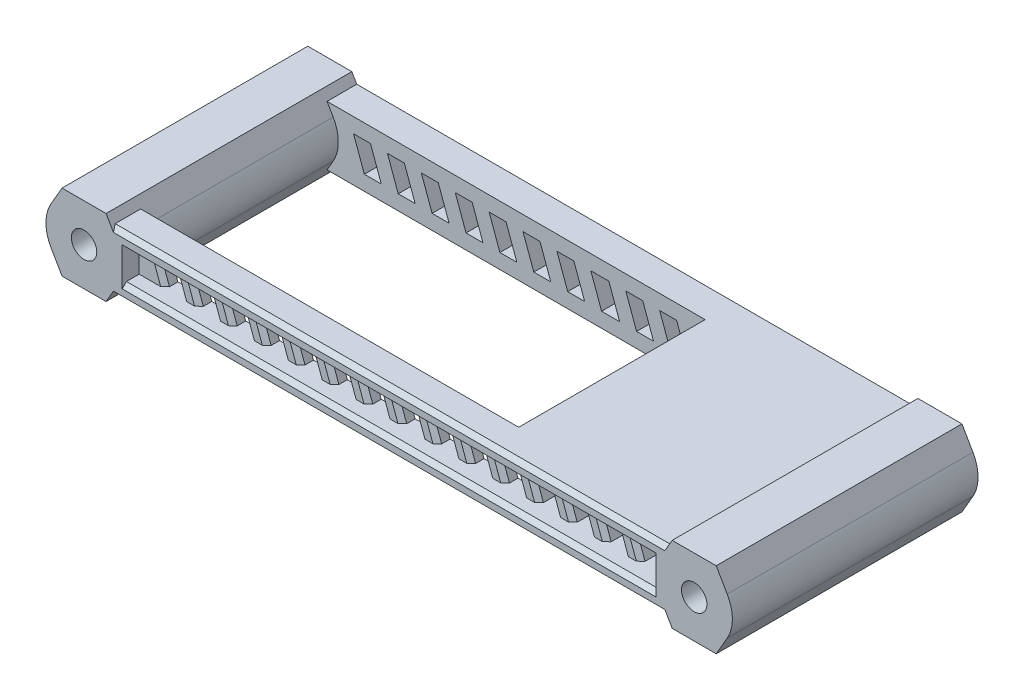
SolidWorks part; units mm, degrees
ref_plane "Front Plane" through (0, 0, 0) normal (0, 0, 1) x (1, 0, 0)
ref_plane "Top Plane" through (0, 0, 0) normal (0, 1, 0) x (1, 0, 0)
ref_plane "Right Plane" through (0, 0, 0) normal (1, 0, 0) x (0, 0, -1)
sketch "Sketch1" plane through (0, 0, 0) normal (0, 0, 1) x (1, 0, 0)
  line L0 (-36, 0) -> (36, 0) construction
  line L1 (0, -10.8775) -> (0, 10.3925) construction
  line L2 (-30.8038, 0) -> (-33.4019, 4.5)
  line L3 (-33.4019, 4.5) -> (-38.5981, 4.5)
  line L4 (-38.5981, 4.5) -> (-41.1962, 0)
  line L5 (-41.1962, 0) -> (-38.5981, -4.5)
  line L6 (-38.5981, -4.5) -> (-33.4019, -4.5)
  line L7 (-33.4019, -4.5) -> (-30.8038, 0)
  line L8 (-32.8246, 3.5) -> (32.8246, 3.5)
  line L9 (32.8246, -3.5) -> (-32.8246, -3.5)
  line L10 (31.5, 1.75) -> (-31.5, 1.75)
  line L11 (-31.5, 1.75) -> (-31.5, -1.75)
  line L12 (-31.5, -1.75) -> (31.5, -1.75)
  line L13 (31.5, 1.75) -> (31.5, -1.75)
  line L14 (33.4019, -4.5) -> (30.8038, 0)
  line L15 (38.5981, -4.5) -> (33.4019, -4.5)
  line L16 (41.1962, 0) -> (38.5981, -4.5)
  line L17 (38.5981, 4.5) -> (41.1962, 0)
  line L18 (33.4019, 4.5) -> (38.5981, 4.5)
  line L19 (30.8038, 0) -> (33.4019, 4.5)
  line L20 (-1.7011, 1.75) -> (-0.4272, -1.75)
  line L21 (0.4272, 1.75) -> (1.7011, -1.75)
  line L22 (-2.4136, 6.6312) -> (2.4136, -6.6312) construction
  line L23 (2.4272, 1.75) -> (3.7011, -1.75)
  line L24 (4.4272, 1.75) -> (5.7011, -1.75)
  line L25 (6.4272, 1.75) -> (7.7011, -1.75)
  line L26 (8.4272, 1.75) -> (9.7011, -1.75)
  line L27 (10.4272, 1.75) -> (11.7011, -1.75)
  line L28 (12.4272, 1.75) -> (13.7011, -1.75)
  line L29 (14.4272, 1.75) -> (15.7011, -1.75)
  line L30 (16.4272, 1.75) -> (17.7011, -1.75)
  line L31 (18.4272, 1.75) -> (19.7011, -1.75)
  line L32 (20.4272, 1.75) -> (21.7011, -1.75)
  line L33 (22.4272, 1.75) -> (23.7011, -1.75)
  line L34 (24.4272, 1.75) -> (25.7011, -1.75)
  line L35 (26.4272, 1.75) -> (27.7011, -1.75)
  line L36 (28.4272, 1.75) -> (29.7011, -1.75)
  line L38 (-3.7011, 1.75) -> (-2.4272, -1.75)
  line L39 (-5.7011, 1.75) -> (-4.4272, -1.75)
  line L40 (-7.7011, 1.75) -> (-6.4272, -1.75)
  line L41 (-9.7011, 1.75) -> (-8.4272, -1.75)
  line L42 (-11.7011, 1.75) -> (-10.4272, -1.75)
  line L43 (-13.7011, 1.75) -> (-12.4272, -1.75)
  line L44 (-15.7011, 1.75) -> (-14.4272, -1.75)
  line L45 (-17.7011, 1.75) -> (-16.4272, -1.75)
  line L46 (-19.7011, 1.75) -> (-18.4272, -1.75)
  line L47 (-21.7011, 1.75) -> (-20.4272, -1.75)
  line L48 (-23.7011, 1.75) -> (-22.4272, -1.75)
  line L49 (-25.7011, 1.75) -> (-24.4272, -1.75)
  line L50 (-27.7011, 1.75) -> (-26.4272, -1.75)
  line L51 (-29.7011, 1.75) -> (-28.4272, -1.75)
  line L53 (-31.7011, 1.75) -> (-30.4272, -1.75)
  line L54 (30.4272, 1.75) -> (31.7011, -1.75)
  circle A0 centre (-36, 0) radius 1.5
  circle A1 centre (-36, 0) radius 4.5 construction
  circle A2 centre (36, 0) radius 4.5 construction
  circle A3 centre (36, 0) radius 1.5
  point P24 (0, -1.75)
  point P25 (0, 1.75)
  point P26 (0, -3.5)
  point P27 (0, 3.5)
  dimension "D1" = 9
  dimension "D2" = 3
  dimension "D3" = 36
  dimension "D4" = 3.5
  dimension "D5" = 1.75
  dimension "D6" = 70
  dimension "D7" = 1
  dimension "D8" = 16
  dimension "D9" = 16
sketch "Sketch2" plane through (0, 0, 0) normal (0, 0, 1) x (1, 0, 0)
  line L0 (32.8246, -3.5) -> (-32.8246, -3.5) construction
  line L3 (-32.8246, 3.5) -> (32.8246, 3.5) construction
  line L4 (-27.7011, 1.75) -> (-26.4272, -1.75) construction
  line L5 (-29.7011, 1.75) -> (-28.4272, -1.75) construction
  line L7 (-36, 0) -> (36, 0) construction
  line L8 (-25.7011, 1.75) -> (-24.4272, -1.75) construction
  line L9 (-23.7011, 1.75) -> (-22.4272, -1.75) construction
  line L10 (-21.7011, 1.75) -> (-20.4272, -1.75) construction
  line L11 (-19.7011, 1.75) -> (-18.4272, -1.75) construction
  line L12 (-17.7011, 1.75) -> (-16.4272, -1.75) construction
  line L13 (-15.7011, 1.75) -> (-14.4272, -1.75) construction
  line L14 (-13.7011, 1.75) -> (-12.4272, -1.75) construction
  line L15 (-11.7011, 1.75) -> (-10.4272, -1.75) construction
  line L16 (-9.7011, 1.75) -> (-8.4272, -1.75) construction
  line L17 (-7.7011, 1.75) -> (-6.4272, -1.75) construction
  line L18 (-5.7011, 1.75) -> (-4.4272, -1.75) construction
  line L19 (-3.7011, 1.75) -> (-2.4272, -1.75) construction
  line L20 (-1.7011, 1.75) -> (-0.4272, -1.75) construction
  line L21 (0, -10.8775) -> (0, 10.3925) construction
  line L22 (0.4272, 1.75) -> (1.7011, -1.75) construction
  line L23 (2.4272, 1.75) -> (3.7011, -1.75) construction
  line L24 (4.4272, 1.75) -> (5.7011, -1.75) construction
  line L25 (6.4272, 1.75) -> (7.7011, -1.75) construction
  line L26 (8.4272, 1.75) -> (9.7011, -1.75) construction
  line L27 (10.4272, 1.75) -> (11.7011, -1.75) construction
  line L28 (12.4272, 1.75) -> (13.7011, -1.75) construction
  line L29 (14.4272, 1.75) -> (15.7011, -1.75) construction
  line L30 (16.4272, 1.75) -> (17.7011, -1.75) construction
  line L31 (18.4272, 1.75) -> (19.7011, -1.75) construction
  line L32 (20.4272, 1.75) -> (21.7011, -1.75) construction
  line L33 (22.4272, 1.75) -> (23.7011, -1.75) construction
  line L34 (24.4272, 1.75) -> (25.7011, -1.75) construction
  line L35 (26.4272, 1.75) -> (27.7011, -1.75) construction
  line L36 (28.4272, 1.75) -> (29.7011, -1.75) construction
  line L38 (-33.4019, -4.5) -> (-30.8038, 0) construction
  line L39 (-38.5981, -4.5) -> (-33.4019, -4.5) construction
  line L40 (-41.1962, 0) -> (-38.5981, -4.5) construction
  line L41 (-38.5981, 4.5) -> (-41.1962, 0) construction
  line L42 (-33.4019, 4.5) -> (-38.5981, 4.5) construction
  line L47 (33.4019, -4.5) -> (30.8038, 0) construction
  line L48 (33.4019, 4.5) -> (38.5981, 4.5) construction
  line L49 (38.5981, 4.5) -> (41.1962, 0) construction
  line L50 (41.1962, 0) -> (38.5981, -4.5) construction
  line L51 (38.5981, -4.5) -> (33.4019, -4.5) construction
  line L52 (32.8246, -3.5) -> (-32.8246, -3.5)
  line L55 (-32.8246, 3.5) -> (32.8246, 3.5)
  line L56 (-27.7011, 1.75) -> (-26.4272, -1.75)
  line L57 (-29.7011, 1.75) -> (-28.4272, -1.75)
  line L59 (-36, 0) -> (36, 0) construction
  line L60 (-25.7011, 1.75) -> (-24.4272, -1.75)
  line L61 (-23.7011, 1.75) -> (-22.4272, -1.75)
  line L62 (-21.7011, 1.75) -> (-20.4272, -1.75)
  line L63 (-19.7011, 1.75) -> (-18.4272, -1.75)
  line L64 (-17.7011, 1.75) -> (-16.4272, -1.75)
  line L65 (-15.7011, 1.75) -> (-14.4272, -1.75)
  line L66 (-13.7011, 1.75) -> (-12.4272, -1.75)
  line L67 (-11.7011, 1.75) -> (-10.4272, -1.75)
  line L68 (-9.7011, 1.75) -> (-8.4272, -1.75)
  line L69 (-7.7011, 1.75) -> (-6.4272, -1.75)
  line L70 (-5.7011, 1.75) -> (-4.4272, -1.75)
  line L71 (-3.7011, 1.75) -> (-2.4272, -1.75)
  line L72 (-1.7011, 1.75) -> (-0.4272, -1.75)
  line L73 (0, -10.8775) -> (0, 10.3925) construction
  line L74 (0.4272, 1.75) -> (1.7011, -1.75)
  line L75 (2.4272, 1.75) -> (3.7011, -1.75)
  line L76 (4.4272, 1.75) -> (5.7011, -1.75)
  line L77 (6.4272, 1.75) -> (7.7011, -1.75)
  line L78 (8.4272, 1.75) -> (9.7011, -1.75)
  line L79 (10.4272, 1.75) -> (11.7011, -1.75)
  line L80 (12.4272, 1.75) -> (13.7011, -1.75)
  line L81 (14.4272, 1.75) -> (15.7011, -1.75)
  line L82 (16.4272, 1.75) -> (17.7011, -1.75)
  line L83 (18.4272, 1.75) -> (19.7011, -1.75)
  line L84 (20.4272, 1.75) -> (21.7011, -1.75)
  line L85 (22.4272, 1.75) -> (23.7011, -1.75)
  line L86 (24.4272, 1.75) -> (25.7011, -1.75)
  line L87 (26.4272, 1.75) -> (27.7011, -1.75)
  line L88 (28.4272, 1.75) -> (29.7011, -1.75)
  line L90 (-33.4019, -4.5) -> (-32.8246, -3.5)
  line L91 (-38.5981, -4.5) -> (-33.4019, -4.5)
  line L92 (-39.8971, -2.25) -> (-38.5981, -4.5)
  line L93 (-38.5981, 4.5) -> (-39.8971, 2.25)
  line L94 (-33.4019, 4.5) -> (-38.5981, 4.5)
  line L95 (28.4272, 1.75) -> (26.4272, 1.75)
  line L98 (27.7011, -1.75) -> (29.7011, -1.75)
  line L99 (33.4019, -4.5) -> (32.8246, -3.5)
  line L100 (33.4019, 4.5) -> (38.5981, 4.5)
  line L101 (38.5981, 4.5) -> (39.8971, 2.25)
  line L102 (39.8971, -2.25) -> (38.5981, -4.5)
  line L103 (38.5981, -4.5) -> (33.4019, -4.5)
  line L104 (-32.8246, 3.5) -> (-33.4019, 4.5)
  line L105 (24.4272, 1.75) -> (22.4272, 1.75)
  line L106 (32.8246, 3.5) -> (33.4019, 4.5)
  line L107 (20.4272, 1.75) -> (18.4272, 1.75)
  line L108 (23.7011, -1.75) -> (25.7011, -1.75)
  line L109 (19.7011, -1.75) -> (21.7011, -1.75)
  line L110 (16.4272, 1.75) -> (14.4272, 1.75)
  line L111 (12.4272, 1.75) -> (10.4272, 1.75)
  line L112 (15.7011, -1.75) -> (17.7011, -1.75)
  line L113 (11.7011, -1.75) -> (13.7011, -1.75)
  line L114 (8.4272, 1.75) -> (6.4272, 1.75)
  line L115 (4.4272, 1.75) -> (2.4272, 1.75)
  line L116 (7.7011, -1.75) -> (9.7011, -1.75)
  line L117 (3.7011, -1.75) -> (5.7011, -1.75)
  line L118 (0.4272, 1.75) -> (-1.7011, 1.75)
  line L119 (-3.7011, 1.75) -> (-5.7011, 1.75)
  line L120 (-0.4272, -1.75) -> (1.7011, -1.75)
  line L121 (-4.4272, -1.75) -> (-2.4272, -1.75)
  line L122 (-7.7011, 1.75) -> (-9.7011, 1.75)
  line L123 (-11.7011, 1.75) -> (-13.7011, 1.75)
  line L124 (-8.4272, -1.75) -> (-6.4272, -1.75)
  line L125 (-12.4272, -1.75) -> (-10.4272, -1.75)
  line L126 (-15.7011, 1.75) -> (-17.7011, 1.75)
  line L127 (-19.7011, 1.75) -> (-21.7011, 1.75)
  line L128 (-16.4272, -1.75) -> (-14.4272, -1.75)
  line L129 (-20.4272, -1.75) -> (-18.4272, -1.75)
  line L130 (-23.7011, 1.75) -> (-25.7011, 1.75)
  line L131 (-27.7011, 1.75) -> (-29.7011, 1.75)
  line L132 (-24.4272, -1.75) -> (-22.4272, -1.75)
  line L133 (-28.4272, -1.75) -> (-26.4272, -1.75)
  circle A0 centre (-36, 0) radius 1.5 construction
  circle A1 centre (-36, 0) radius 4.5 construction
  circle A3 centre (-36, 0) radius 1.5
  arc A4 (-39.8971, 2.25) -> (-39.8971, -2.25) centre (-36, 0) ccw
  circle A5 centre (36, 0) radius 1.5 construction
  arc A6 (39.8971, -2.25) -> (39.8971, 2.25) centre (36, 0) ccw
  circle A7 centre (36, 0) radius 1.5
extrude "Boss-Extrude1" add sketch "Sketch2" along normal blind 27
sketch "Sketch3" plane through (0, 0, 27) normal (0, 0, 1) x (1, 0, 0)
  line L0 (-41.1962, 0) -> (-38.5981, -4.5) construction
  line L1 (-38.5981, -4.5) -> (-33.4019, -4.5) construction
  line L2 (-33.4019, -4.5) -> (-30.8038, 0) construction
  line L3 (-30.8038, 0) -> (-33.4019, 4.5) construction
  line L4 (-33.4019, 4.5) -> (-38.5981, 4.5) construction
  line L5 (-38.5981, 4.5) -> (-41.1962, 0) construction
  line L6 (-31.5, 1.75) -> (-31.5, -1.75) construction
  line L7 (-31.5, -1.75) -> (31.5, -1.75) construction
  line L8 (31.5, 1.75) -> (-31.5, 1.75) construction
  line L9 (-32.8246, 3.5) -> (32.8246, 3.5) construction
  line L10 (32.8246, -3.5) -> (-32.8246, -3.5) construction
  line L11 (33.4019, -4.5) -> (30.8038, 0) construction
  line L12 (38.5981, -4.5) -> (33.4019, -4.5) construction
  line L13 (41.1962, 0) -> (38.5981, -4.5) construction
  line L14 (38.5981, 4.5) -> (41.1962, 0) construction
  line L15 (33.4019, 4.5) -> (38.5981, 4.5) construction
  line L17 (31.5, 1.75) -> (31.5, -1.75) construction
  line L18 (-36, 0) -> (36, 0) construction
  line L19 (0, -10.8775) -> (0, 10.3925) construction
  line L20 (-39.8971, -2.25) -> (-38.5981, -4.5)
  line L21 (-38.5981, -4.5) -> (-33.4019, -4.5)
  line L22 (-33.4019, -4.5) -> (-32.8246, -3.5)
  line L23 (-32.8246, 3.5) -> (-33.4019, 4.5)
  line L24 (-33.4019, 4.5) -> (-38.5981, 4.5)
  line L25 (-38.5981, 4.5) -> (-39.8971, 2.25)
  line L26 (-31.5, 1.75) -> (-31.5, -1.75)
  line L27 (-31.5, -1.75) -> (31.5, -1.75)
  line L28 (31.5, 1.75) -> (-31.5, 1.75)
  line L29 (-32.8246, 3.5) -> (32.8246, 3.5)
  line L30 (32.8246, -3.5) -> (-32.8246, -3.5)
  line L31 (33.4019, -4.5) -> (32.8246, -3.5)
  line L32 (38.5981, -4.5) -> (33.4019, -4.5)
  line L33 (39.8971, -2.25) -> (38.5981, -4.5)
  line L34 (38.5981, 4.5) -> (39.8971, 2.25)
  line L35 (33.4019, 4.5) -> (38.5981, 4.5)
  line L37 (31.5, 1.75) -> (31.5, -1.75)
  line L38 (-36, 0) -> (36, 0) construction
  line L39 (0, -10.8775) -> (0, 10.3925) construction
  line L41 (32.8246, 3.5) -> (33.4019, 4.5)
  circle A0 centre (-36, 0) radius 4.5 construction
  circle A1 centre (-36, 0) radius 1.5 construction
  circle A3 centre (36, 0) radius 1.5 construction
  arc A4 (-39.8971, 2.25) -> (-39.8971, -2.25) centre (-36, 0) ccw
  circle A5 centre (-36, 0) radius 1.5
  circle A7 centre (36, 0) radius 1.5
  arc A8 (39.8971, -2.25) -> (39.8971, 2.25) centre (36, 0) ccw
extrude "Boss-Extrude2" add sketch "Sketch3" along normal blind 2
chamfer "Chamfer1" distance 0.5 angle 45 34 edges at (29.0642, 0, 27) (27.0642, 0, 27) (25.0642, 0, 27) (23.0642, 0, 27) (21.0642, 0, 27) (19.0642, 0, 27) (17.0642, 0, 27) (15.0642, 0, 27) (13.0642, 0, 27) (11.0642, 0, 27) (9.0642, 0, 27) (7.0642, 0, 27) (5.0642, 0, 27) (3.0642, 0, 27) (1.0642, 0, 27) (-1.0642, 0, 27) (-3.0642, 0, 27) (-5.0642, 0, 27) (-7.0642, 0, 27) (-9.0642, 0, 27) (-11.0642, 0, 27) (-13.0642, 0, 27) (-15.0642, 0, 27) (-17.0642, 0, 27) (-19.0642, 0, 27) (-21.0642, 0, 27) (-23.0642, 0, 27) (-25.0642, 0, 27) (-27.0642, 0, 27) (-29.0642, 0, 27) (0, -3.5, 29) (0, -1.75, 29) (0, 1.75, 29) (0, 3.5, 29)
ref_plane "Plane1" through (0, 0, 14.5) normal (0, 0, 1) x (1, 0, 0)
sketch "Sketch4" plane through (0, 0, 14.5) normal (0, 0, 1) x (1, 0, 0)
  line L0 (-33.4019, -4.5) -> (-30.8038, 0) construction
  line L1 (-30.8038, 0) -> (-33.4019, 4.5) construction
  line L2 (-33.4019, 4.5) -> (-34.8445, 6.9986)
  line L3 (-32.1029, 2.25) -> (-33.4019, 4.5)
  line L4 (-33.4019, -4.5) -> (-34.8445, -6.9986)
  line L5 (-34.8445, 6.9986) -> (10.5169, 6.9986)
  line L6 (-33.4019, -4.5) -> (-32.1029, -2.25)
  line L7 (-34.8445, -6.9986) -> (15.6115, -6.9986)
  line L8 (12.4272, 1.75) -> (10.5169, 6.9986)
  line L9 (13.7011, -1.75) -> (15.6115, -6.9986)
  line L10 (-36, 0) -> (36, 0) construction
  line L11 (-36, 0) -> (36, 0) construction
  line L12 (12.4272, 1.75) -> (13.7011, -1.75) construction
  line L13 (12.4272, 1.75) -> (13.7011, -1.75)
  circle A0 centre (-36, 0) radius 4.5 construction
  arc A1 (-32.1029, -2.25) -> (-32.1029, 2.25) centre (-36, 0) ccw
  dimension "D1" = 6.9986
extrude "Cut-Extrude1" cut sketch "Sketch4" against normal mid plane 22
